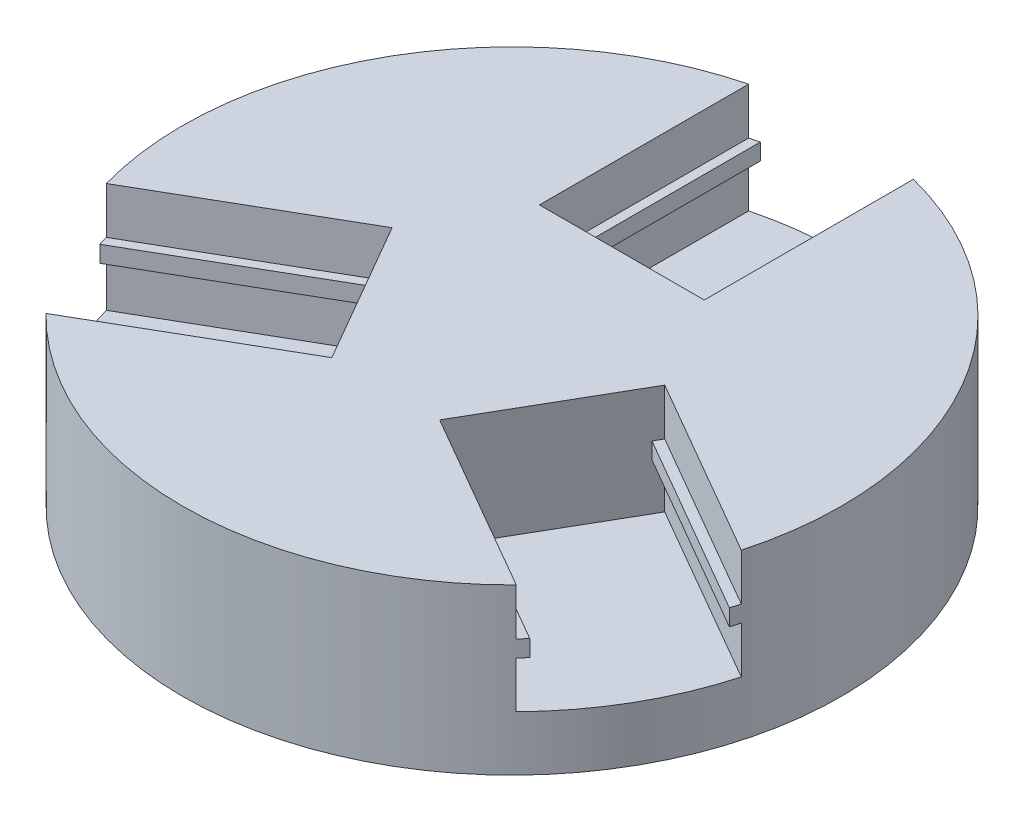
SolidWorks part; units mm, degrees
material "Custom Plastic"
ref_plane "Front Plane" through (0, 0, 0) normal (0, 0, 1) x (1, 0, 0)
ref_plane "Top Plane" through (0, 0, 0) normal (0, 1, 0) x (1, 0, 0)
ref_plane "Right Plane" through (0, 0, 0) normal (1, 0, 0) x (0, 0, -1)
sketch "Sketch1" plane through (0, 0, 0) normal (0, 1, 0) x (1, 0, 0)
  circle A0 centre (0, 0) radius 30
  dimension "D1" = 60
extrude "Boss-Extrude1" add sketch "Sketch1" along normal blind 15
sketch "Sketch3" plane through (0, 15, 0) normal (0, 1, 0) x (1, 0, 0)
  line L0 (0, -30) -> (0, 30) construction
  line L1 (0, 0) -> (-21.2132, -21.2132) construction
  line L2 (0, 0) -> (21.2132, -21.2132) construction
  circle A0 centre (0, 0) radius 30 construction
  dimension "D1" = 45
  dimension "D2" = 45
ref_plane "Plane4" through (0, 15, -30) normal (0, 0, -1) x (-1, 0, 0)
sketch "Sketch4" plane through (0, 15, -30) normal (0, 0, -1) x (-1, 0, 0)
  line L0 (-7.5, -10) -> (-7.5, -5.75)
  line L1 (-7.5, -10) -> (7.5, -10)
  line L2 (-7.5, 0) -> (7.5, 0)
  line L3 (7.5, -10) -> (7.5, -5.75)
  line L4 (-7.5, -10) -> (7.5, 0) construction
  line L5 (-7.5, 0) -> (7.5, -10) construction
  line L6 (-6.65, -5) -> (6.65, -5) construction
  line L7 (-6.65, -4.25) -> (-6.65, -5.75)
  line L8 (-6.65, -4.25) -> (-7.5, -4.25)
  line L9 (-6.65, -5.75) -> (-7.5, -5.75)
  line L11 (0, 0) -> (0, -10) construction
  line L12 (6.65, -5.75) -> (7.5, -5.75)
  line L13 (6.65, -4.25) -> (7.5, -4.25)
  line L14 (6.65, -4.25) -> (6.65, -5.75)
  line L15 (-7.5, -4.25) -> (-7.5, 0)
  line L16 (7.5, -4.25) -> (7.5, 0)
  point P0 (0, 0)
  point P2 (0, 0)
  point P3 (0, -5)
  point P5 (0, -5)
  point P15 (-6.65, -5)
  dimension "D1" = 15
  dimension "D2" = 10
  dimension "D3" = 1.5
  dimension "D4" = 0.85
extrude "Cut-Extrude1" cut sketch "Sketch4" against normal blind 20
pattern_circular "CirPattern1" count 3 over 360 about axis through (0, 0, 0) along (0, 1, 0) of "Cut-Extrude1"
equation "\"D2@Sketch3\"=\"D1@Sketch3\""
